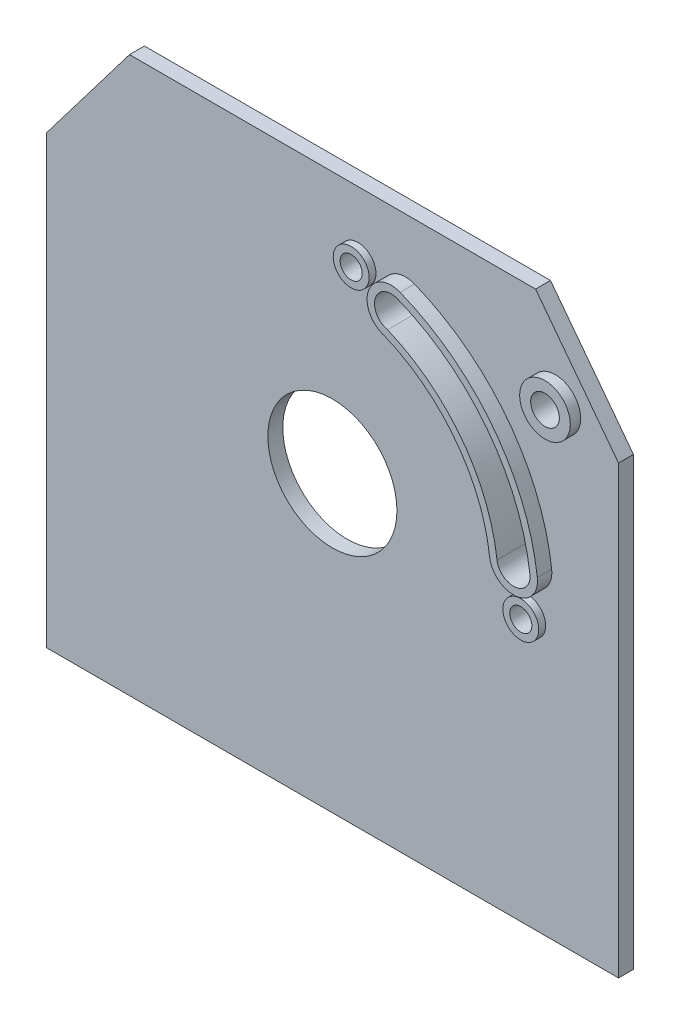
SolidWorks part; units mm, degrees
ref_plane "Front Plane" through (0, 0, 0) normal (0, 0, 1) x (1, 0, 0)
ref_plane "Top Plane" through (0, 0, 0) normal (0, 1, 0) x (1, 0, 0)
ref_plane "Right Plane" through (0, 0, 0) normal (1, 0, 0) x (0, 0, -1)
sketch "Sketch1" plane through (0, 0, 0) normal (0, 0, 1) x (1, 0, 0)
  line L0 (122.0182, 78.9322) -> (103.6651, 103.0902)
  line L1 (-4.5387, -19.7473) -> (122.0182, -19.7473)
  line L2 (-4.5387, 78.9322) -> (13.8145, 103.0902)
  line L3 (-4.5387, -19.7473) -> (-4.5387, 78.9322)
  line L4 (122.0182, -19.7473) -> (122.0182, 78.9322)
  line L5 (58.7102, 45.2839) -> (108.0314, 83.2746) construction
  line L6 (13.8145, 103.0902) -> (103.6651, 103.0902)
  line L7 (25.2805, 88.6839) -> (58.7102, 45.2839) construction
  line L8 (58.7102, 45.2839) -> (126.6162, 45.2839) construction
  circle A0 centre (58.7102, 45.2839) radius 14.2802
  arc A1 (105.5849, 50.9789) -> (76.2585, 89.1214) centre (58.7102, 45.2839) ccw
  arc A2 (76.2585, 89.1214) -> (74.0707, 82.0997) centre (74.8907, 85.6959) ccw
  arc A3 (98.3115, 50.0887) -> (105.5849, 50.9789) centre (101.9482, 50.5338) ccw
  arc A4 (98.3115, 50.0887) -> (74.0707, 82.0997) centre (58.7102, 45.2839) ccw
  circle A5 centre (108.0314, 83.2746) radius 3.175
  circle A7 centre (64.386, 88.4087) radius 2.4459
  circle A8 centre (101.9144, 39.6877) radius 2.4459
  point P23 (58.7398, -19.7473)
  dimension "D1" = 127.606
extrude "Extrude1" add sketch "Sketch1" along normal blind 3.302
ref_plane "Plane2" through (-12.3952, -9.549, 0) normal (0.7922, 0.6103, 0) x (-0.6103, 0.7922, 0)
ref_plane "Plane3" through (58.7366, 45.2496, 0) normal (0.7922, 0.6103, 0) x (0, 0, -1)
ref_plane "Plane4" through (0, 0, 3.302) normal (0, 0, 1) x (1, 0, 0)
sketch "Sketch2" plane through (0, 0, 3.302) normal (0, 0, 1) x (1, 0, 0)
  arc A0 (96.6726, 49.889) -> (73.5521, 80.5269) centre (58.7102, 45.2839) ccw
  arc A3 (76.8714, 90.6545) -> (73.5521, 80.5269) centre (74.8907, 85.6959) ccw
  arc A4 (107.2238, 51.1787) -> (76.8714, 90.6545) centre (58.7102, 45.2839) ccw
  arc A6 (96.6726, 49.889) -> (107.2238, 51.1787) centre (101.9482, 50.5338) ccw
  arc A10 (98.3115, 50.0887) -> (105.5849, 50.9789) centre (101.9482, 50.5338) ccw construction
  arc A11 (98.3115, 50.0887) -> (74.0707, 82.0997) centre (58.7102, 45.2839) ccw construction
  arc A12 (76.2585, 89.1214) -> (74.0707, 82.0997) centre (74.8907, 85.6959) ccw construction
  arc A13 (105.5849, 50.9789) -> (76.2585, 89.1214) centre (58.7102, 45.2839) ccw construction
  arc A14 (98.3115, 50.0887) -> (105.5849, 50.9789) centre (101.9482, 50.5338) ccw
  arc A15 (98.3115, 50.0887) -> (74.0707, 82.0997) centre (58.7102, 45.2839) ccw
  arc A16 (76.2585, 89.1214) -> (74.0707, 82.0997) centre (74.8907, 85.6959) ccw
  arc A17 (105.5849, 50.9789) -> (76.2585, 89.1214) centre (58.7102, 45.2839) ccw
  dimension "D1" = 1.651
extrude "Extrude2" add sketch "Sketch2" along normal blind 3.175
sketch "Sketch3" plane through (0, 0, 3.302) normal (0, 0, 1) x (1, 0, 0)
  circle A0 centre (64.386, 88.4087) radius 2.4459 construction
  circle A1 centre (101.9144, 39.6877) radius 2.4459 construction
  circle A2 centre (64.386, 88.4087) radius 2.4459
  circle A3 centre (101.9144, 39.6877) radius 2.4459
  circle A4 centre (64.386, 88.4087) radius 3.9699
  circle A5 centre (101.9144, 39.6877) radius 3.9699
  dimension "D1" = 1.524
extrude "Extrude3" add sketch "Sketch3" along normal blind 1.524
sketch "Sketch4" plane through (0, 0, 3.302) normal (0, 0, 1) x (1, 0, 0)
  circle A0 centre (108.0314, 83.2746) radius 3.175 construction
  circle A1 centre (108.0314, 83.2746) radius 3.175
  circle A2 centre (108.0314, 83.2746) radius 5.6046
extrude "Extrude4" add sketch "Sketch4" along normal blind 2.286
